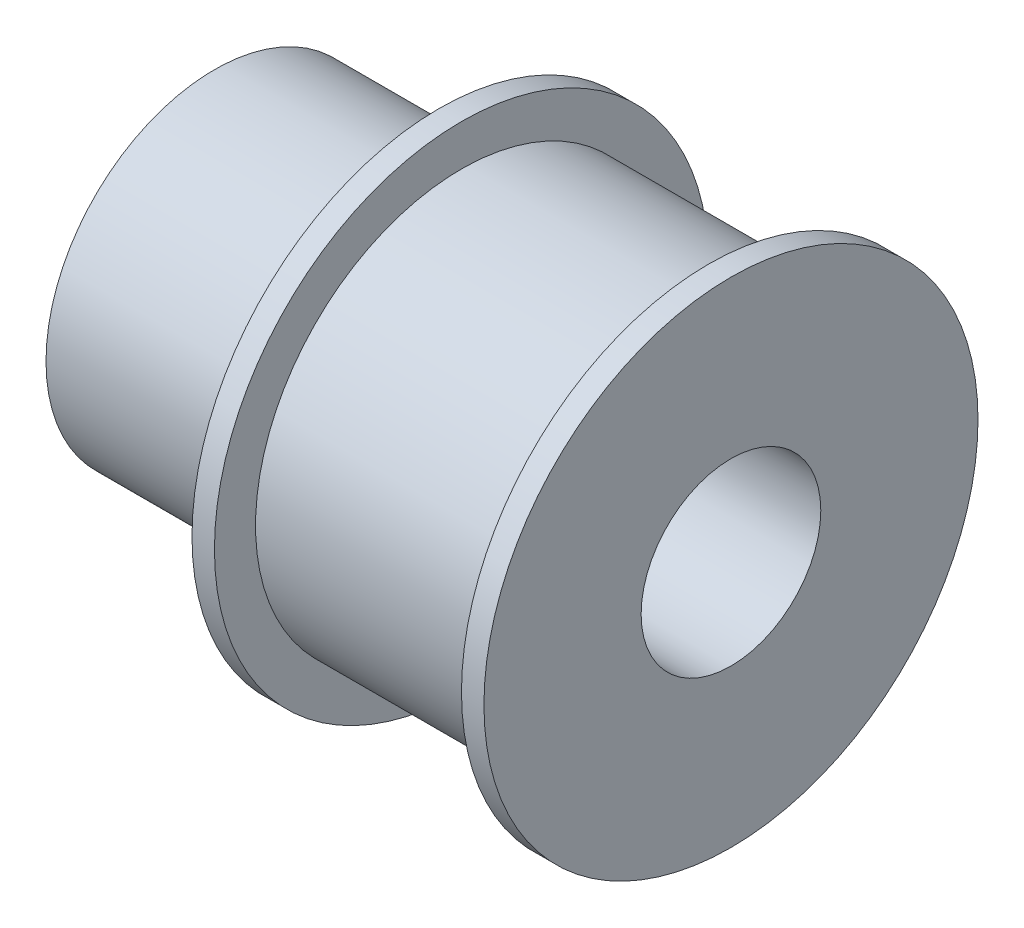
SolidWorks part; units mm, degrees
ref_plane "前视基准面" through (0, 0, 0) normal (0, 0, 1) x (1, 0, 0)
ref_plane "上视基准面" through (0, 0, 0) normal (0, 1, 0) x (1, 0, 0)
ref_plane "右视基准面" through (0, 0, 0) normal (1, 0, 0) x (0, 0, -1)
other "Configuration Table"
sketch "草图1" plane through (0, 0, 0) normal (1, 0, 0) x (0, 0, -1)
  circle A1 centre (0, 0) radius 11
  dimension "D1" = 22
extrude "凸台-拉伸1" add sketch "草图1" along normal blind 13
ref_plane "基准面1" through (6.5, 0, 0) normal (1, 0, 0) x (0, 0, -1)
sketch "草图2" plane through (6.5, 0, 0) normal (1, 0, 0) x (0, 0, -1)
  circle A0 centre (0, 0) radius 9.17
  circle A1 centre (0, 0) radius 11
extrude "切除-拉伸1" cut sketch "草图2" against normal mid plane 11
sketch "草图3" plane through (0, 0, 0) normal (-1, 0, 0) x (0, 0, 1)
  circle A0 centre (0, 0) radius 7.5
extrude "凸台-拉伸2" add sketch "草图3" along normal blind 10
sketch "草图4" plane through (-10, 0, 0) normal (-1, 0, 0) x (0, 0, 1)
  circle A0 centre (0, 0) radius 4
extrude "切除-拉伸2" cut sketch "草图4" against normal up to next
